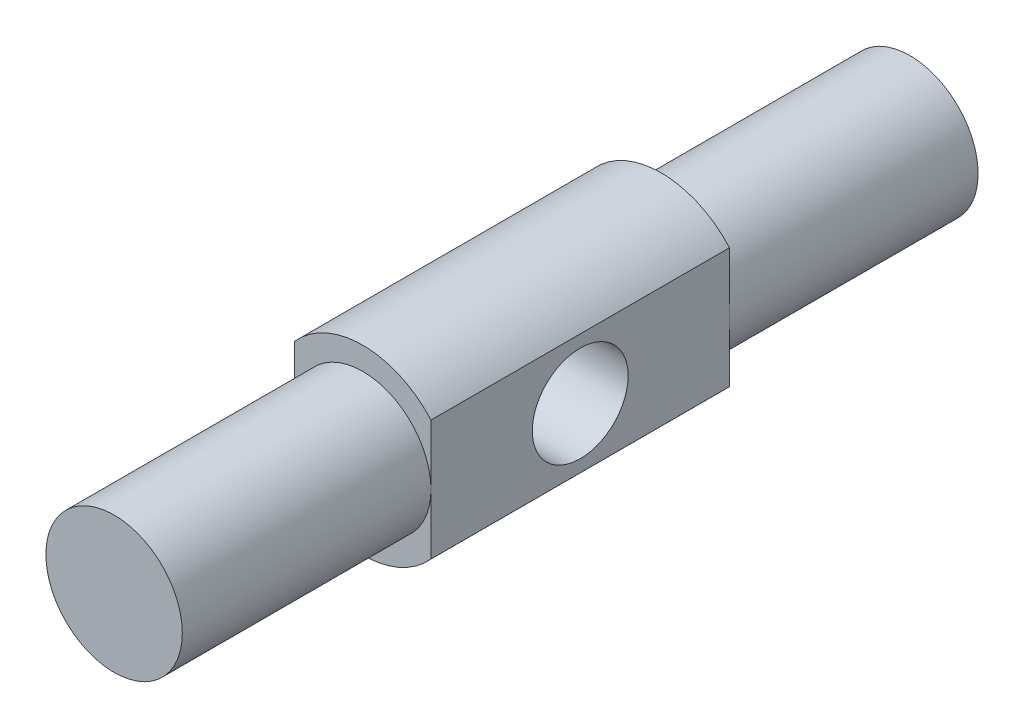
SolidWorks part; units mm, degrees
ref_plane "Front Plane" through (0, 0, 0) normal (0, 0, 1) x (1, 0, 0)
ref_plane "Top Plane" through (0, 0, 0) normal (0, 1, 0) x (1, 0, 0)
ref_plane "Right Plane" through (0, 0, 0) normal (1, 0, 0) x (0, 0, -1)
sketch "Sketch2" plane through (0, 0, 0) normal (0, 0, 1) x (1, 0, 0)
  line L0 (6, 0) -> (6, 5.2915)
  line L1 (6, 0) -> (6, -5.2915)
  line L2 (-6, 0) -> (-6, 5.2915)
  line L3 (-6, 0) -> (-6, -5.2915)
  circle A0 centre (0, 0) radius 6
  arc A1 (-6, -5.2915) -> (6, -5.2915) centre (0, 0) ccw
  arc A2 (6, 5.2915) -> (-6, 5.2915) centre (0, 0) ccw
  dimension "D1" = 12
  dimension "D2" = 16
extrude "Boss-Extrude2" add sketch "Sketch2" against normal blind 70 contours L0 A2 L2 A0 | A0 | L3 A1 L1 A0
sketch "Sketch4" plane through (6, 0, 0) normal (1, 0, 0) x (0, 0, -1)
  line L0 (35, 8) -> (35, -8) construction
  line L1 (70, 8) -> (0, 8) construction
  line L2 (0, -8) -> (70, -8) construction
  line L15 (21.875, 8) -> (48.125, -8) construction
  line L16 (21.875, 8) -> (48.125, 8)
  line L17 (21.875, 8) -> (21.875, -8)
  line L18 (21.875, -8) -> (48.125, -8)
  line L19 (48.125, 8) -> (48.125, -8)
  line L20 (21.875, 8) -> (25.875, 8) construction
  circle A0 centre (35, 0) radius 4.215
  point P11 (35, 0)
  point P15 (35, 0)
  dimension "D2" = 8.43
  dimension "D1" = 26.25
sketch "Sketch5" plane through (0, 0, 0) normal (0, 0, 1) x (1, 0, 0)
  line L0 (-6, 5.2915) -> (-6, -5.2915)
  line L1 (6, 5.2915) -> (6, -5.2915)
  circle A0 centre (0, 0) radius 6
  arc A1 (-6, -5.2915) -> (6, -5.2915) centre (0, 0) ccw
  arc A2 (6, 5.2915) -> (-6, 5.2915) centre (0, 0) ccw
  line M6 (6, -5.2915) -> (6, 5.2915)
  arc M7 (6, 5.2915) -> (-6, 5.2915) centre (0, 0) ccw
  line M8 (-6, 5.2915) -> (-6, -5.2915)
  arc M9 (-6, -5.2915) -> (6, -5.2915) centre (0, 0) ccw
  dimension "D1" = 12
extrude "Cut-Extrude1" cut sketch "Sketch5" against normal blind 21.875 contours A0 L1 M7 M8 | A0 L0 M9 M6
sketch "Sketch6" plane through (0, 0, -70) normal (0, 0, -1) x (-1, 0, 0)
  line L0 (-6, 5.2915) -> (-6, -5.2915)
  line L1 (6, 5.2915) -> (6, -5.2915)
  circle A0 centre (0, 0) radius 6
  arc A1 (-6, -5.2915) -> (6, -5.2915) centre (0, 0) ccw
  arc A2 (6, 5.2915) -> (-6, 5.2915) centre (0, 0) ccw
  line M6 (-6, 5.2915) -> (-6, -5.2915)
  arc M7 (-6, -5.2915) -> (6, -5.2915) centre (0, 0) ccw
  line M8 (6, -5.2915) -> (6, 5.2915)
  arc M9 (6, 5.2915) -> (-6, 5.2915) centre (0, 0) ccw
  dimension "D1" = 12
extrude "Cut-Extrude3" cut sketch "Sketch6" against normal blind 21.875 contours A0 L1 M9 M6 | A0 L0 M7 M8
extrude "Cut-Extrude4" cut sketch "Sketch4" against normal through all contours A0
sketch "Sketch7" plane through (6, 0, 0) normal (1, 0, 0) x (0, 0, -1)
  line L1 (48.125, 8) -> (21.875, 8) construction
  line L2 (21.875, 0) -> (48.125, 0) construction
  circle A1 centre (25.875, 8) radius 1
  dimension "D2" = 2
  dimension "D1" = 4
equation "\"Shaft Diameter\"= 12"
equation "\"Brace Diameter\"= 16"
equation "\"Shaft Length\"= 70"
equation "\"D1@Sketch2\"=\"Shaft Diameter\""
equation "\"D2@Sketch2\"=\"Brace Diameter\""
equation "\"D1@Sketch4\"=\"Shaft Length\"*3/8"
equation "\"D1@Sketch5\"=\"Shaft Diameter\""
equation "\"D1@Cut-Extrude1\"=\"Shaft Length\"*2.5/8"
equation "\"D1@Sketch6\"=\"Shaft Diameter\""
equation "\"D1@Cut-Extrude3\"=\"Shaft Length\"*2.5/8"
equation "\"D1@Sketch7\"=\"Brace Diameter\"-\"Shaft Diameter\""
equation "\"D2@Sketch7\"=(\"Brace Diameter\"-\"Shaft Diameter\")/2"
